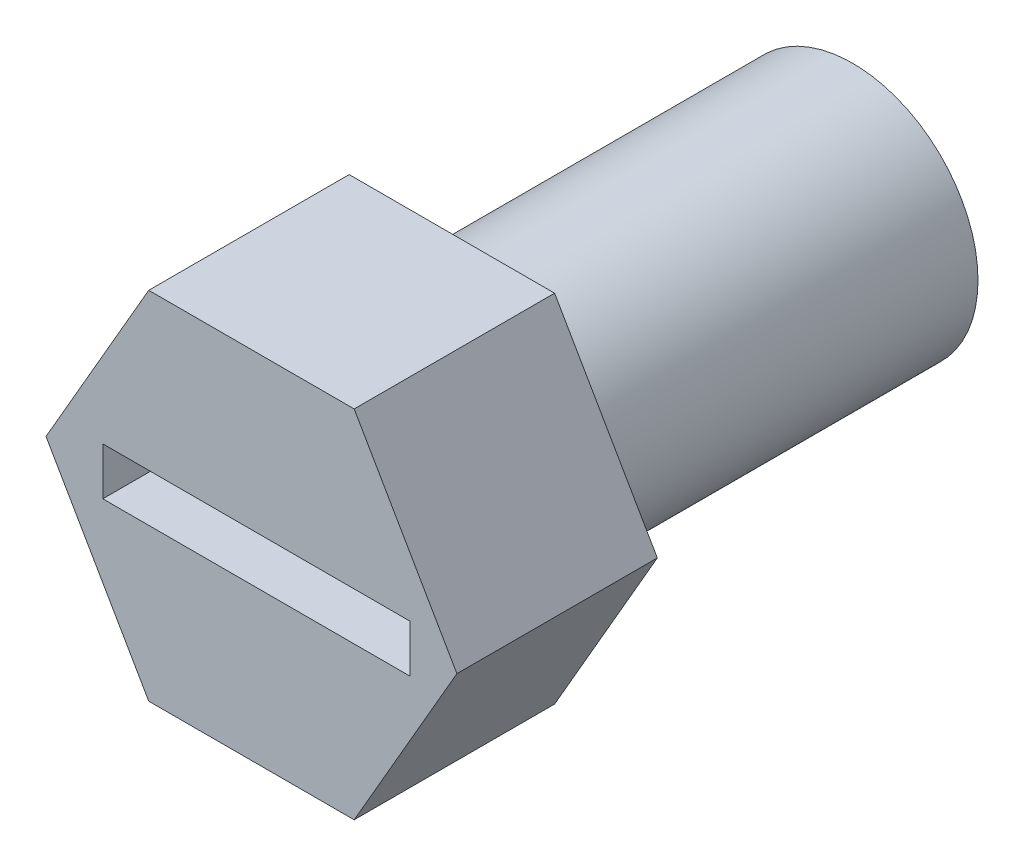
SolidWorks part; units mm, degrees
ref_plane "Front Plane" through (0, 0, 0) normal (0, 0, 1) x (1, 0, 0)
ref_plane "Top Plane" through (0, 0, 0) normal (0, 1, 0) x (1, 0, 0)
ref_plane "Right Plane" through (0, 0, 0) normal (1, 0, 0) x (0, 0, -1)
sketch "Sketch1" plane through (0, 0, 0) normal (0, 0, 1) x (1, 0, 0)
  circle A0 centre (0, 0) radius 12.5
  dimension "D1" = 25
extrude "Boss-Extrude1" add sketch "Sketch1" along normal blind 40
sketch "Sketch2" plane through (0, 0, 40) normal (0, 0, 1) x (1, 0, 0)
  line L1 (20.5012, 0) -> (10.2506, 17.7546)
  line L2 (10.2506, 17.7546) -> (-10.2506, 17.7546)
  line L3 (-10.2506, 17.7546) -> (-20.5012, 0)
  line L4 (-20.5012, 0) -> (-10.2506, -17.7546)
  line L5 (-10.2506, -17.7546) -> (10.2506, -17.7546)
  line L6 (10.2506, -17.7546) -> (20.5012, 0)
  circle A0 centre (0, 0) radius 17.7546 construction
extrude "Boss-Extrude2" add sketch "Sketch2" along normal blind 20
sketch "Sketch3" plane through (0, 0, 60) normal (0, 0, 1) x (1, 0, 0)
  line L1 (-14.8335, 2.1962) -> (15.8416, 2.1962)
  line L2 (-14.8335, 2.1962) -> (-14.8335, -2.5563)
  line L3 (-14.8335, -2.5563) -> (15.8416, -2.5563)
  line L4 (15.8416, 2.1962) -> (15.8416, -2.5563)
extrude "Cut-Extrude1" cut sketch "Sketch3" against normal blind 15
